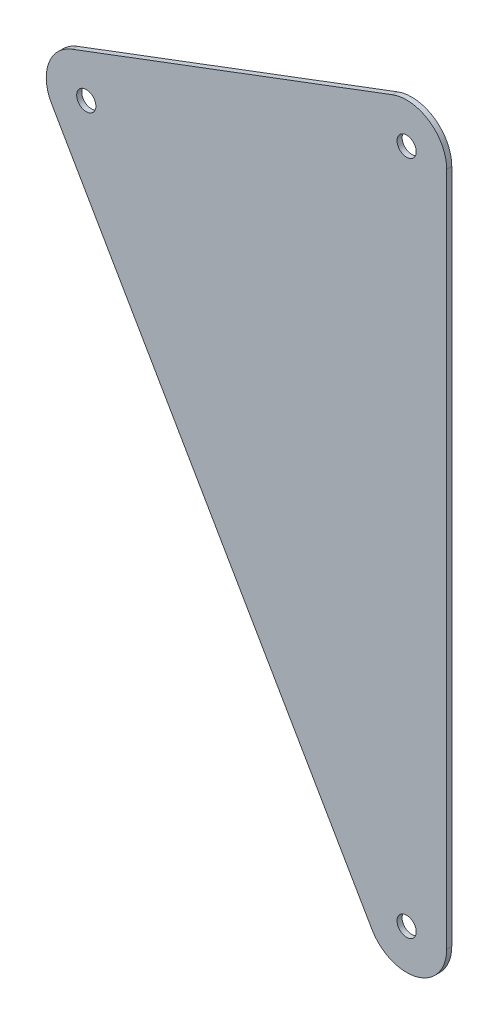
SolidWorks part; units mm, degrees
ref_plane "Front Plane" through (0, 0, 0) normal (0, 0, 1) x (1, 0, 0)
ref_plane "Top Plane" through (0, 0, 0) normal (0, 1, 0) x (1, 0, 0)
ref_plane "Right Plane" through (0, 0, 0) normal (1, 0, 0) x (0, 0, -1)
sketch "Sketch1" plane through (0, 0, 0) normal (0, 0, 1) x (1, 0, 0)
  line L0 (-110.8253, 166.9551) -> (-10.8253, -6.25)
  line L1 (12.5, 0) -> (12.5, 210.8897)
  line L2 (-4.408, 222.5867) -> (-104.408, 184.9021)
  line L3 (-100, 173.2051) -> (0, 173.2051) construction
  line L4 (0, 173.2051) -> (0, 0) construction
  line L5 (-100, 173.2051) -> (0, 0) construction
  line L7 (0, 210.8897) -> (0, 173.2051) construction
  arc A0 (-10.8253, -6.25) -> (12.5, 0) centre (0, 0) ccw
  arc A1 (-104.408, 184.9021) -> (-110.8253, 166.9551) centre (-100, 173.2051) ccw
  arc A2 (12.5, 210.8897) -> (-4.408, 222.5867) centre (0, 210.8897) ccw
  circle A3 centre (-100, 173.2051) radius 3
  circle A4 centre (0, 210.8897) radius 3
  circle A5 centre (0, 0) radius 3
  dimension "D1" = 12.5
  dimension "D2" = 6
  dimension "D3" = 200
  dimension "D4" = 173.2051
  dimension "D5" = 20.649
extrude "Boss-Extrude1" add sketch "Sketch1" along normal blind 1.5875
